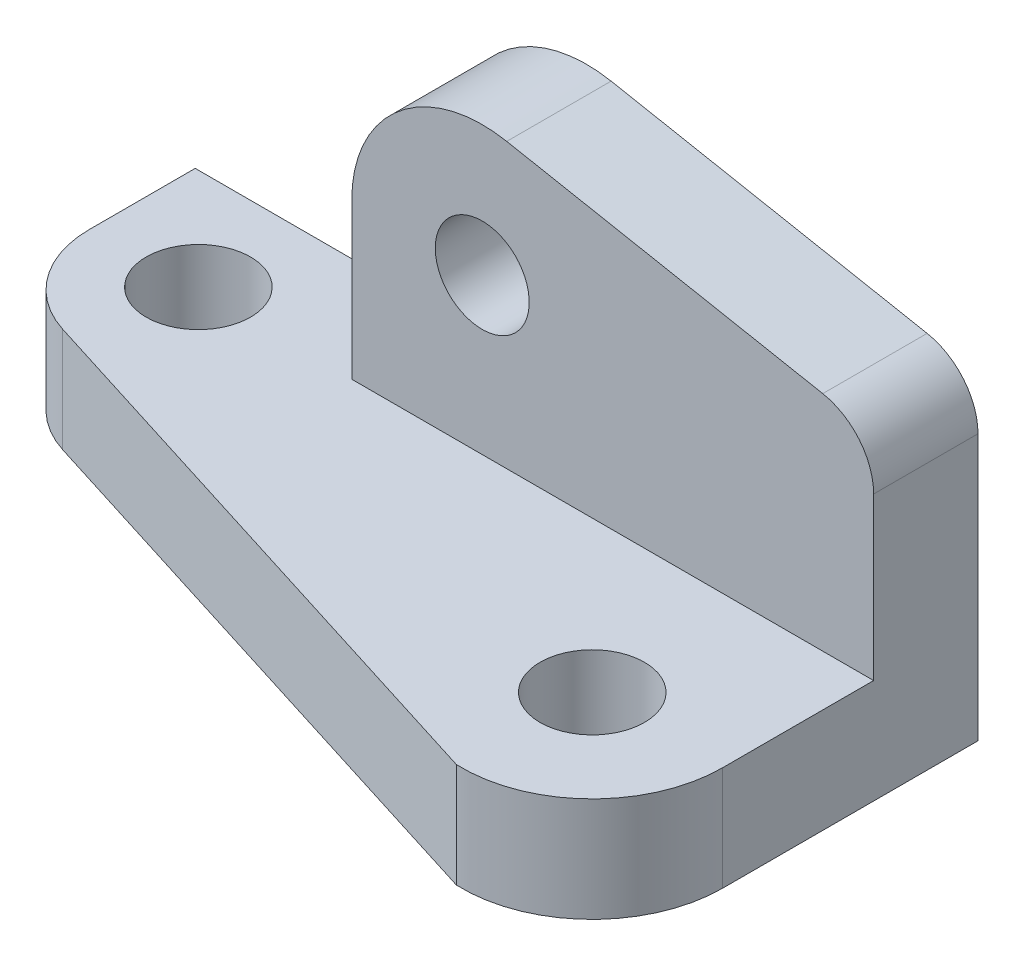
SolidWorks part; units mm, degrees
ref_plane "前基準面" through (0, 0, 0) normal (0, 0, 1) x (1, 0, 0)
ref_plane "上基準面" through (0, 0, 0) normal (0, 1, 0) x (1, 0, 0)
ref_plane "右基準面" through (0, 0, 0) normal (1, 0, 0) x (0, 0, -1)
sketch "草圖1" plane through (0, 0, 0) normal (0, 1, 0) x (1, 0, 0)
  line L0 (0, 0) -> (150, 0)
  line L1 (150, 0) -> (150, -48.9374)
  line L3 (0, -20.3163) -> (0, 0)
  line L4 (14.0095, -39.3981) -> (123.9599, -73.9157)
  circle A0 centre (20, -19.3981) radius 10
  circle A1 centre (125, -48.9157) radius 10
  arc A2 (150, -48.9374) -> (123.9599, -73.9157) centre (125, -48.9374) cw
  arc A3 (14.0095, -39.3981) -> (0, -20.3163) centre (20, -20.3163) cw
  point P11 (0, -35)
  point P14 (150, -75)
  point P17 (125.1268, -61.5827)
  dimension "D1" = 75
  dimension "D2" = 35
  dimension "D3" = 20
  dimension "D4" = 20
  dimension "D6" = 25
  dimension "D7" = 20
  dimension "D12" = 109.9504
  dimension "D5" = 150
  dimension "D8" = 25
  dimension "D9" = 25
  dimension "D10" = 20
  dimension "D11" = 20
  dimension "D13" = 20.3163
extrude "填料-伸長1" add sketch "草圖1" along normal blind 20
sketch "草圖3" plane through (0, 0, 0) normal (0, 0, -1) x (-1, 0, 0)
  line L0 (-150, 20) -> (-150, 50.9561)
  line L1 (-140.2537, 62.7426) -> (-79.6952, 74.322)
  line L2 (-50, 49.7668) -> (-50, 20)
  line L3 (-50, 20) -> (-150, 20)
  arc A0 (-50, 49.7668) -> (-79.6952, 74.322) centre (-75, 49.7668) ccw
  arc A1 (-140.2537, 62.7426) -> (-150, 50.9561) centre (-138, 50.9561) ccw
  circle A3 centre (-75, 49.7668) radius 9
  point P9 (-50, 80)
  point P12 (-150, 60.879)
  dimension "D3" = 25
  dimension "D4" = 100
  dimension "D5" = 12.9757
  dimension "D6" = 18
  dimension "D1" = 12
  dimension "D2" = 80
extrude "填料-伸長3" add sketch "草圖3" against normal blind 20
